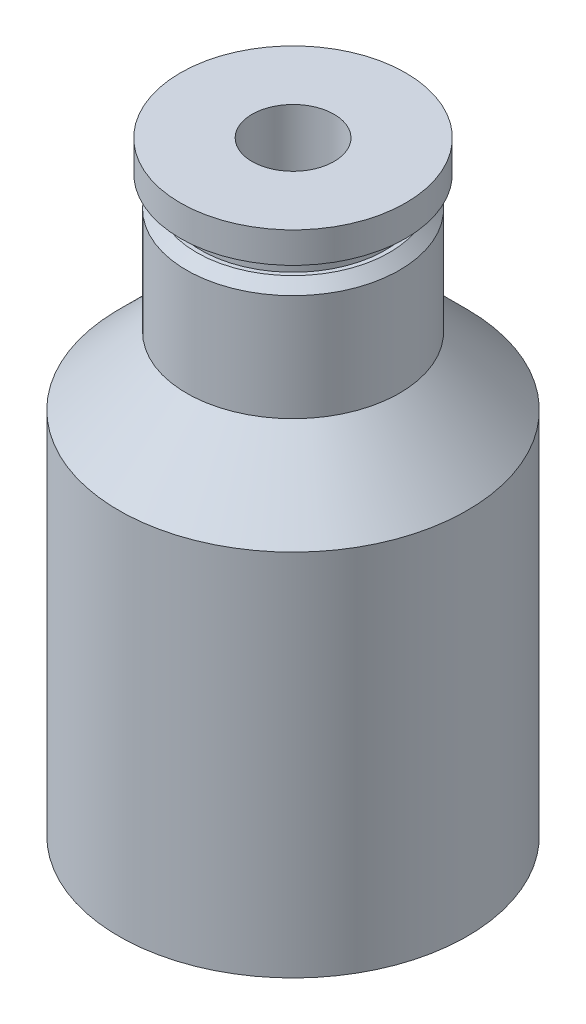
SolidWorks part; units mm, degrees
ref_plane "Спереди" through (0, 0, 0) normal (0, 0, 1) x (1, 0, 0)
ref_plane "Сверху" through (0, 0, 0) normal (0, 1, 0) x (1, 0, 0)
ref_plane "Справа" through (0, 0, 0) normal (1, 0, 0) x (0, 0, -1)
sketch "Эскиз1" plane through (0, 0, 0) normal (0, 0, 1) x (1, 0, 0)
  line L0 (0, 0) -> (0, 29.5) construction
  line L1 (2, 29.5) -> (2, 13.0443)
  line L2 (2, 29.5) -> (5.5, 29.5)
  line L3 (5.5, 29.5) -> (5.5, 28)
  line L4 (5.5, 28) -> (4.5, 28)
  line L5 (4.5, 28) -> (4.5, 27)
  line L6 (4.5, 27) -> (4.7, 27)
  line L7 (4.7, 27) -> (5.1962, 26.5038)
  line L8 (5.1962, 26.5038) -> (5.1962, 21.3038)
  line L9 (5.1962, 21.3038) -> (8.5, 18)
  line L10 (8.5, 18) -> (8.5, 0)
  line L11 (8.5, 0) -> (6, 0)
  line L12 (6, 0) -> (6, 10)
  line L13 (6, 10) -> (2, 10)
  line L14 (2, 13.0443) -> (2, 10)
  line L16 (5.1962, 23.27) -> (2.5981, 27.77) construction
  line L17 (2.5981, 27.77) -> (-2.5981, 27.77) construction
  line L18 (-2.5981, 27.77) -> (-5.1962, 23.27) construction
  line L19 (-5.1962, 23.27) -> (-2.5981, 18.77) construction
  line L20 (-2.5981, 18.77) -> (2.5981, 18.77) construction
  line L21 (2.5981, 18.77) -> (5.1962, 23.27) construction
  circle A0 centre (0, 23.27) radius 4.5 construction
  point P5 (7.25, 0)
  dimension "D1" = 4
  dimension "D2" = 11
  dimension "D3" = 29.5
  dimension "D4" = 1.5
  dimension "D5" = 1
  dimension "D6" = 1
  dimension "D7" = 10
  dimension "D8" = 12
  dimension "D9" = 17
  dimension "D10" = 9
  dimension "D11" = 45
  dimension "D12" = 18
  dimension "D13" = 0.2
revolve "Повернуть1" add sketch "Эскиз1" angle 360 about L0
